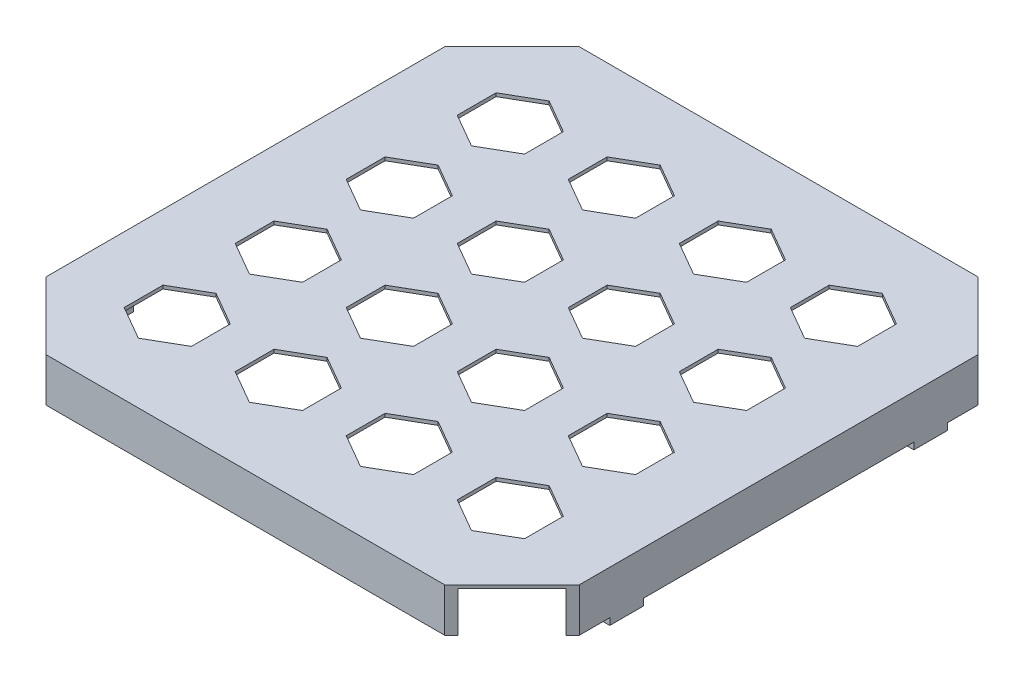
SolidWorks part; units mm, degrees
ref_plane "Front Plane" through (0, 0, 0) normal (0, 0, 1) x (1, 0, 0)
ref_plane "Top Plane" through (0, 0, 0) normal (0, 1, 0) x (1, 0, 0)
ref_plane "Right Plane" through (0, 0, 0) normal (1, 0, 0) x (0, 0, -1)
sketch "Sketch1" plane through (0, 0, 0) normal (0, 1, 0) x (1, 0, 0)
  line L0 (0, 138.5) -> (20, 158.5)
  line L1 (0, 0) -> (158.5, 0)
  line L2 (0, 0) -> (0, 158.5)
  line L3 (0, 158.5) -> (158.5, 158.5)
  line L4 (158.5, 0) -> (158.5, 158.5)
  line L5 (79.25, 158.5) -> (79.25, 0) construction
  line L6 (158.5, 79.25) -> (0, 79.25) construction
  line L7 (158.5, 138.5) -> (138.5, 158.5)
  line L8 (158.5, 20) -> (138.5, 0)
  line L9 (0, 20) -> (20, 0)
  dimension "D1" = 158.5
  dimension "D2" = 158.5
  dimension "D3" = 45
  dimension "D4" = 20
extrude "Boss-Extrude1" add sketch "Sketch1" along normal blind 13 contours L2 L9 L1 L8 L4 L7 L3 L0
sketch "Sketch5" plane through (0, 0, 0) normal (0, -1, 0) x (1, 0, 0)
  line L0 (0, -20) -> (0, -138.5) construction
  line L1 (2, -2) -> (156.5, -2)
  line L2 (2, -2) -> (2, -156.5)
  line L3 (2, -156.5) -> (156.5, -156.5)
  line L4 (156.5, -2) -> (156.5, -156.5)
  line L5 (20, 0) -> (138.5, 0) construction
  dimension "D1" = 2
  dimension "D2" = 2
  dimension "D3" = 154.5
extrude "Cut-Extrude3" cut sketch "Sketch5" against normal blind 12
sketch "Sketch7" plane through (0, 13, 0) normal (0, 1, 0) x (1, 0, 0)
  line L0 (158.5, 20) -> (158.5, 138.5) construction
  line L1 (138.5, 122.7265) -> (138.5, 134.2735)
  line L2 (138.5, 134.2735) -> (128.5, 140.047)
  line L3 (128.5, 140.047) -> (118.5, 134.2735)
  line L4 (118.5, 134.2735) -> (118.5, 122.7265)
  line L5 (118.5, 122.7265) -> (128.5, 116.953)
  line L6 (128.5, 116.953) -> (138.5, 122.7265)
  line L7 (20, 158.5) -> (138.5, 158.5) construction
  line L9 (105.5, 122.7265) -> (105.5, 134.2735)
  line L10 (105.5, 134.2735) -> (95.5, 140.047)
  line L11 (95.5, 140.047) -> (85.5, 134.2735)
  line L12 (85.5, 134.2735) -> (85.5, 122.7265)
  line L13 (85.5, 122.7265) -> (95.5, 116.953)
  line L14 (95.5, 116.953) -> (105.5, 122.7265)
  line L15 (72.5, 122.7265) -> (72.5, 134.2735)
  line L16 (72.5, 134.2735) -> (62.5, 140.047)
  line L17 (62.5, 140.047) -> (52.5, 134.2735)
  line L18 (52.5, 134.2735) -> (52.5, 122.7265)
  line L19 (52.5, 122.7265) -> (62.5, 116.953)
  line L20 (62.5, 116.953) -> (72.5, 122.7265)
  line L21 (39.5, 122.7265) -> (39.5, 134.2735)
  line L22 (39.5, 134.2735) -> (29.5, 140.047)
  line L23 (29.5, 140.047) -> (19.5, 134.2735)
  line L24 (19.5, 134.2735) -> (19.5, 122.7265)
  line L25 (19.5, 122.7265) -> (29.5, 116.953)
  line L26 (29.5, 116.953) -> (39.5, 122.7265)
  line L27 (105.5, 89.7265) -> (105.5, 101.2735)
  line L28 (105.5, 101.2735) -> (95.5, 107.047)
  line L29 (95.5, 107.047) -> (85.5, 101.2735)
  line L30 (85.5, 101.2735) -> (85.5, 89.7265)
  line L31 (85.5, 89.7265) -> (95.5, 83.953)
  line L32 (95.5, 83.953) -> (105.5, 89.7265)
  line L33 (72.5, 89.7265) -> (72.5, 101.2735)
  line L34 (72.5, 101.2735) -> (62.5, 107.047)
  line L35 (62.5, 107.047) -> (52.5, 101.2735)
  line L36 (52.5, 101.2735) -> (52.5, 89.7265)
  line L37 (52.5, 89.7265) -> (62.5, 83.953)
  line L38 (62.5, 83.953) -> (72.5, 89.7265)
  line L39 (39.5, 89.7265) -> (39.5, 101.2735)
  line L40 (39.5, 101.2735) -> (29.5, 107.047)
  line L41 (29.5, 107.047) -> (19.5, 101.2735)
  line L42 (19.5, 101.2735) -> (19.5, 89.7265)
  line L43 (19.5, 89.7265) -> (29.5, 83.953)
  line L44 (29.5, 83.953) -> (39.5, 89.7265)
  line L45 (105.5, 56.7265) -> (105.5, 68.2735)
  line L46 (105.5, 68.2735) -> (95.5, 74.047)
  line L47 (95.5, 74.047) -> (85.5, 68.2735)
  line L48 (85.5, 68.2735) -> (85.5, 56.7265)
  line L49 (85.5, 56.7265) -> (95.5, 50.953)
  line L50 (95.5, 50.953) -> (105.5, 56.7265)
  line L51 (72.5, 56.7265) -> (72.5, 68.2735)
  line L52 (72.5, 68.2735) -> (62.5, 74.047)
  line L53 (62.5, 74.047) -> (52.5, 68.2735)
  line L54 (52.5, 68.2735) -> (52.5, 56.7265)
  line L55 (52.5, 56.7265) -> (62.5, 50.953)
  line L56 (62.5, 50.953) -> (72.5, 56.7265)
  line L57 (39.5, 56.7265) -> (39.5, 68.2735)
  line L58 (39.5, 68.2735) -> (29.5, 74.047)
  line L59 (29.5, 74.047) -> (19.5, 68.2735)
  line L60 (19.5, 68.2735) -> (19.5, 56.7265)
  line L61 (19.5, 56.7265) -> (29.5, 50.953)
  line L62 (29.5, 50.953) -> (39.5, 56.7265)
  line L63 (105.5, 23.7265) -> (105.5, 35.2735)
  line L64 (105.5, 35.2735) -> (95.5, 41.047)
  line L65 (95.5, 41.047) -> (85.5, 35.2735)
  line L66 (85.5, 35.2735) -> (85.5, 23.7265)
  line L67 (85.5, 23.7265) -> (95.5, 17.953)
  line L68 (95.5, 17.953) -> (105.5, 23.7265)
  line L69 (72.5, 23.7265) -> (72.5, 35.2735)
  line L70 (72.5, 35.2735) -> (62.5, 41.047)
  line L71 (62.5, 41.047) -> (52.5, 35.2735)
  line L72 (52.5, 35.2735) -> (52.5, 23.7265)
  line L73 (52.5, 23.7265) -> (62.5, 17.953)
  line L74 (62.5, 17.953) -> (72.5, 23.7265)
  line L75 (39.5, 23.7265) -> (39.5, 35.2735)
  line L76 (39.5, 35.2735) -> (29.5, 41.047)
  line L77 (29.5, 41.047) -> (19.5, 35.2735)
  line L78 (19.5, 35.2735) -> (19.5, 23.7265)
  line L79 (19.5, 23.7265) -> (29.5, 17.953)
  line L80 (29.5, 17.953) -> (39.5, 23.7265)
  line L81 (138.5, 89.7265) -> (138.5, 101.2735)
  line L82 (138.5, 101.2735) -> (128.5, 107.047)
  line L83 (128.5, 107.047) -> (118.5, 101.2735)
  line L84 (118.5, 101.2735) -> (118.5, 89.7265)
  line L85 (118.5, 89.7265) -> (128.5, 83.953)
  line L86 (128.5, 83.953) -> (138.5, 89.7265)
  line L87 (138.5, 56.7265) -> (138.5, 68.2735)
  line L88 (138.5, 68.2735) -> (128.5, 74.047)
  line L89 (128.5, 74.047) -> (118.5, 68.2735)
  line L90 (118.5, 68.2735) -> (118.5, 56.7265)
  line L91 (118.5, 56.7265) -> (128.5, 50.953)
  line L92 (128.5, 50.953) -> (138.5, 56.7265)
  line L93 (138.5, 23.7265) -> (138.5, 35.2735)
  line L94 (138.5, 35.2735) -> (128.5, 41.047)
  line L95 (128.5, 41.047) -> (118.5, 35.2735)
  line L96 (118.5, 35.2735) -> (118.5, 23.7265)
  line L97 (118.5, 23.7265) -> (128.5, 17.953)
  line L98 (128.5, 17.953) -> (138.5, 23.7265)
  circle A0 centre (128.5, 128.5) radius 10 construction
  dimension "D2" = 20
  dimension "D1" = 30
  dimension "D3" = 30
  dimension "D4" = 4
  dimension "D5" = 4
extrude "Cut-Extrude4" cut sketch "Sketch7" against normal blind 11
sketch "Sketch8" plane through (0, 0, 0) normal (0, -1, 0) x (1, 0, 0)
  line L0 (0, -20) -> (0, -138.5) construction
  line L1 (0, -29.0544) -> (5, -29.0544)
  line L2 (0, -29.0544) -> (0, -39.0544)
  line L3 (0, -39.0544) -> (5, -39.0544)
  line L4 (5, -29.0544) -> (5, -39.0544)
  line L5 (0, -79.25) -> (158.5, -79.25) construction
  line L6 (158.5, -20) -> (158.5, -138.5) construction
  line L7 (0, -129.4456) -> (5, -129.4456)
  line L8 (0, -129.4456) -> (0, -119.4456)
  line L9 (0, -119.4456) -> (5, -119.4456)
  line L10 (5, -129.4456) -> (5, -119.4456)
  line L11 (79.25, 0) -> (79.25, -158.5) construction
  line L12 (20, 0) -> (138.5, 0) construction
  line L13 (20, -158.5) -> (138.5, -158.5) construction
  line L14 (158.5, -129.4456) -> (158.5, -119.4456)
  line L15 (158.5, -119.4456) -> (153.5, -119.4456)
  line L16 (153.5, -129.4456) -> (153.5, -119.4456)
  line L17 (158.5, -129.4456) -> (153.5, -129.4456)
  line L18 (158.5, -39.0544) -> (153.5, -39.0544)
  line L19 (153.5, -29.0544) -> (153.5, -39.0544)
  line L20 (158.5, -29.0544) -> (153.5, -29.0544)
  line L21 (158.5, -29.0544) -> (158.5, -39.0544)
  dimension "D1" = 10
  dimension "D2" = 5
extrude "Boss-Extrude2" add sketch "Sketch8" along normal blind 2
sketch "Sketch9" plane through (5, 0, 0) normal (1, 0, 0) x (0, 0, -1)
  line L0 (39.0544, -2) -> (119.4456, -2) construction
  line L1 (119.4456, -2) -> (129.4456, -2)
  line L2 (119.4456, -2) -> (119.4456, 3)
  line L3 (119.4456, 3) -> (129.4456, 3)
  line L4 (129.4456, -2) -> (129.4456, 3)
  line L5 (79.25, -2) -> (79.25, 4.691) construction
  line L6 (79.25, 4.691) -> (79.25, -7.6689) construction
  line L7 (39.0544, 3) -> (29.0544, 3)
  line L8 (29.0544, -2) -> (29.0544, 3)
  line L9 (39.0544, -2) -> (29.0544, -2)
  line L10 (39.0544, -2) -> (39.0544, 3)
  dimension "D1" = 10
  dimension "D2" = 5
extrude "Boss-Extrude3" add sketch "Sketch9" along normal blind 2
sketch "Sketch11" plane through (153.5, 0, 0) normal (-1, 0, 0) x (0, 0, 1)
  line L0 (-119.4456, -2) -> (-39.0544, -2) construction
  line L1 (-129.4456, -2) -> (-119.4456, -2)
  line L2 (-129.4456, -2) -> (-129.4456, 2.3005)
  line L3 (-129.4456, 2.3005) -> (-119.4456, 2.3005)
  line L4 (-119.4456, -2) -> (-119.4456, 2.3005)
  line L5 (-79.25, -2) -> (-79.25, 4.7069) construction
  line L6 (-79.25, 4.7069) -> (-79.25, -10.7258) construction
  line L7 (-29.0544, 2.3005) -> (-39.0544, 2.3005)
  line L8 (-39.0544, -2) -> (-39.0544, 2.3005)
  line L9 (-29.0544, -2) -> (-39.0544, -2)
  line L10 (-29.0544, -2) -> (-29.0544, 2.3005)
extrude "Boss-Extrude4" add sketch "Sketch11" along normal blind 2
